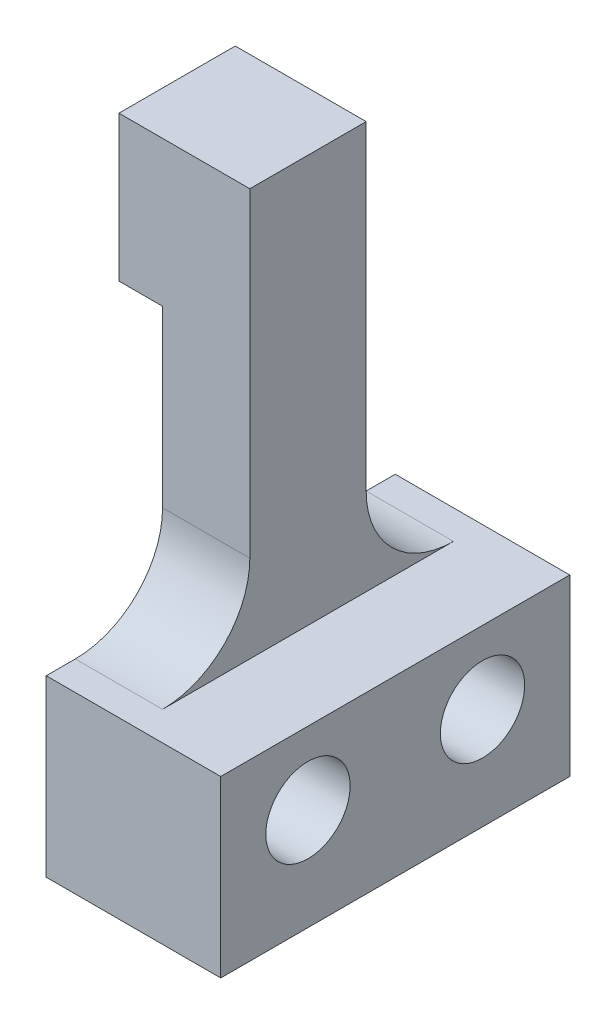
SolidWorks part; units mm, degrees
ref_plane "Front Plane" through (0, 0, 0) normal (0, 0, 1) x (1, 0, 0)
ref_plane "Top Plane" through (0, 0, 0) normal (0, 1, 0) x (1, 0, 0)
ref_plane "Right Plane" through (0, 0, 0) normal (1, 0, 0) x (0, 0, -1)
sketch "Sketch1" plane through (0, 0, 0) normal (0, 0, 1) x (1, 0, 0)
  line L0 (0, 21.3158) -> (0, -26.0526) construction
  line L1 (0, -6.8684) -> (-6, -6.8684)
  line L2 (-6, -6.8684) -> (-6, 8.1316)
  line L3 (-6, 8.1316) -> (-7.5, 8.1316)
  line L4 (-7.5, 8.1316) -> (-7.5, 13.1316)
  line L5 (-7.5, 13.1316) -> (-3, 13.1316)
  line L6 (-3, 13.1316) -> (-3, -0.8684)
  line L7 (-3, -0.8684) -> (0, -0.8684)
  line L8 (0, -0.8684) -> (0, -6.8684)
  dimension "D1" = 6
  dimension "D2" = 5
  dimension "D3" = 20
  dimension "D4" = 3
  dimension "D5" = 6
  dimension "D6" = 1.5
extrude "Boss-Extrude1" add sketch "Sketch1" along normal blind 12
sketch "Sketch2" plane through (-3, 0, 0) normal (1, 0, 0) x (0, 0, -1)
  line L0 (-12, -0.8684) -> (0, -0.8684) construction
  line L1 (-12.9369, 14.2112) -> (-8, 14.2112)
  line L2 (-12.9369, 14.2112) -> (-12.9369, -0.8684)
  line L3 (-12.9369, -0.8684) -> (-8, -0.8684)
  line L4 (-8, 14.2112) -> (-8, -0.8684)
  line L5 (-12, -6.8684) -> (-12, -0.8684) construction
  line L6 (-4, 14.2112) -> (1.2929, 14.2112)
  line L7 (-4, 14.2112) -> (-4, -0.8684)
  line L8 (-4, -0.8684) -> (1.2929, -0.8684)
  line L9 (1.2929, 14.2112) -> (1.2929, -0.8684)
  dimension "D1" = 4
  dimension "D2" = 4
extrude "Cut-Extrude1" cut sketch "Sketch2" against normal through all
fillet "Fillet1" radius 3 2 edges at (-4.5, -0.8684, 8) (-4.5, -0.8684, 4)
hole_wizard "M2.5 Clearance Hole1" positions "Sketch3" profile "Sketch4" hole size "M2.5" standard "ANSI Metric" end condition through all
sketch "Sketch3" plane through (-6, 0, 0) normal (-1, 0, 0) x (0, 0, 1)
  line L0 (12, -6.8684) -> (0, -6.8684) construction
  line L1 (0, -0.8684) -> (0, -6.8684) construction
  point P0 (3, -3.3684)
  point P2 (9, -3.3684)
  dimension "D1" = 6
  dimension "D2" = 3.5
  dimension "D3" = 3
sketch "Sketch4" plane through (-6, -3.3684, 3) normal (0, 1, 0) x (0, 0, 1)
  line L0 (0, 0) -> (0, 6)
  line L1 (0, 6) -> (1.45, 6)
  line L2 (1.45, 6) -> (1.45, 0)
  line L5 (1.45, 0) -> (0, 0)
  line L11 (0, -6.35) -> (0, 107.95) construction
  dimension "Thru Hole Dia." = 2.9
  dimension "Thru Hole Depth" = 6
